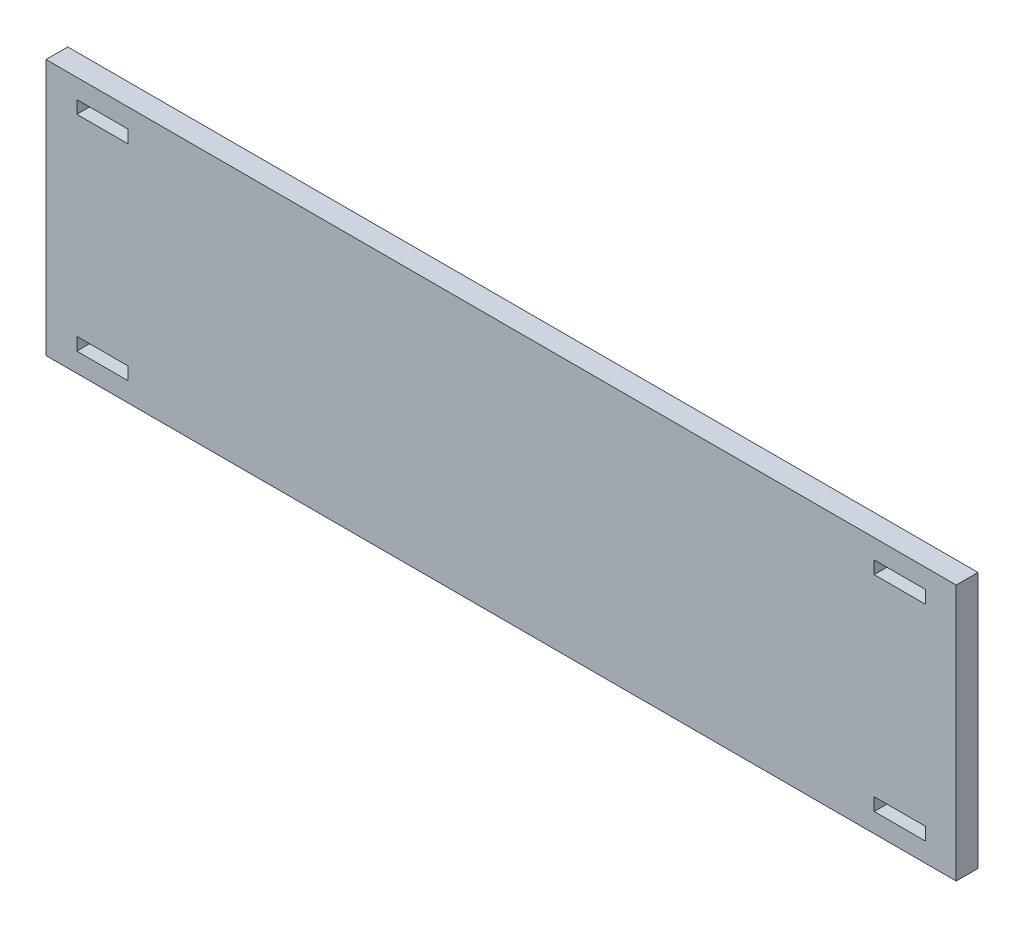
SolidWorks part; units mm, degrees
ref_plane "Alzado" through (0, 0, 0) normal (0, 0, 1) x (1, 0, 0)
ref_plane "Planta" through (0, 0, 0) normal (0, 1, 0) x (1, 0, 0)
ref_plane "Vista lateral" through (0, 0, 0) normal (1, 0, 0) x (0, 0, -1)
sketch "Croquis2" plane through (0, 0, 0) normal (0, 0, 1) x (1, 0, 0)
  line L0 (-97.5, 50) -> (-97.5, -50) construction
  line L1 (-177.5, 50) -> (177.5, 50)
  line L2 (-177.5, 50) -> (-177.5, -50)
  line L3 (-177.5, -50) -> (177.5, -50)
  line L4 (177.5, 50) -> (177.5, -50)
  line L5 (-177.5, 50) -> (177.5, -50) construction
  line L6 (-177.5, -50) -> (177.5, 50) construction
  line L7 (0, 50) -> (0, -50) construction
  line L8 (97.5, 50) -> (97.5, -50) construction
  point P0 (0, 0)
  dimension "D1" = 100
  dimension "D2" = 355
  dimension "D3" = 80
  dimension "D4" = 80
extrude "Saliente-Extruir1" add sketch "Croquis2" along normal blind 8.5
ref_plane "Plano1" through (0, 0, 8.5) normal (0, 0, 1) x (1, 0, 0)
sketch "Croquis4" plane through (0, 0, 8.5) normal (0, 0, 1) x (1, 0, 0)
  line L0 (-155.5, 50) -> (-155.5, -50) construction
  line L1 (177.5, 50) -> (-177.5, 50) construction
  line L2 (-177.5, -50) -> (177.5, -50) construction
  line L3 (155.5, 50) -> (155.5, -50) construction
  line L4 (-177.5, 50) -> (-177.5, -50) construction
  line L5 (177.5, -50) -> (177.5, 50) construction
  line L6 (-177.5, 0) -> (177.5, 0) construction
  line L8 (-165.5, 42.5) -> (-145.5, 42.5)
  line L9 (-165.5, 42.5) -> (-165.5, 37.5)
  line L10 (-165.5, 37.5) -> (-145.5, 37.5)
  line L11 (-145.5, 42.5) -> (-145.5, 37.5)
  line L12 (-165.5, 42.5) -> (-145.5, 37.5) construction
  line L13 (-165.5, 37.5) -> (-145.5, 42.5) construction
  line L14 (-165.5, -37.5) -> (-145.5, -37.5)
  line L15 (-165.5, -37.5) -> (-165.5, -42.5)
  line L16 (-165.5, -42.5) -> (-145.5, -42.5)
  line L17 (-145.5, -37.5) -> (-145.5, -42.5)
  line L18 (-165.5, -37.5) -> (-145.5, -42.5) construction
  line L19 (-165.5, -42.5) -> (-145.5, -37.5) construction
  line L20 (145.5, 42.5) -> (165.5, 42.5)
  line L21 (145.5, 42.5) -> (145.5, 37.5)
  line L22 (145.5, 37.5) -> (165.5, 37.5)
  line L23 (165.5, 42.5) -> (165.5, 37.5)
  line L24 (145.5, 42.5) -> (165.5, 37.5) construction
  line L25 (145.5, 37.5) -> (165.5, 42.5) construction
  line L26 (145.5, -37.5) -> (165.5, -37.5)
  line L27 (145.5, -37.5) -> (145.5, -42.5)
  line L28 (145.5, -42.5) -> (165.5, -42.5)
  line L29 (165.5, -37.5) -> (165.5, -42.5)
  line L30 (145.5, -37.5) -> (165.5, -42.5) construction
  line L31 (145.5, -42.5) -> (165.5, -37.5) construction
  point P14 (-155.5, 40)
  point P19 (-155.5, -40)
  point P24 (155.5, 40)
  point P29 (155.5, -40)
  dimension "D1" = 22
  dimension "D2" = 22
  dimension "D3" = 20
  dimension "D4" = 5
  dimension "D5" = 40
  dimension "D6" = 40
  dimension "D7" = 20
  dimension "D8" = 5
  dimension "D9" = 40
  dimension "D10" = 20
  dimension "D11" = 5
  dimension "D12" = 40
  dimension "D13" = 20
  dimension "D14" = 5
extrude "Cortar-Extruir1" cut sketch "Croquis4" against normal blind 6.5
